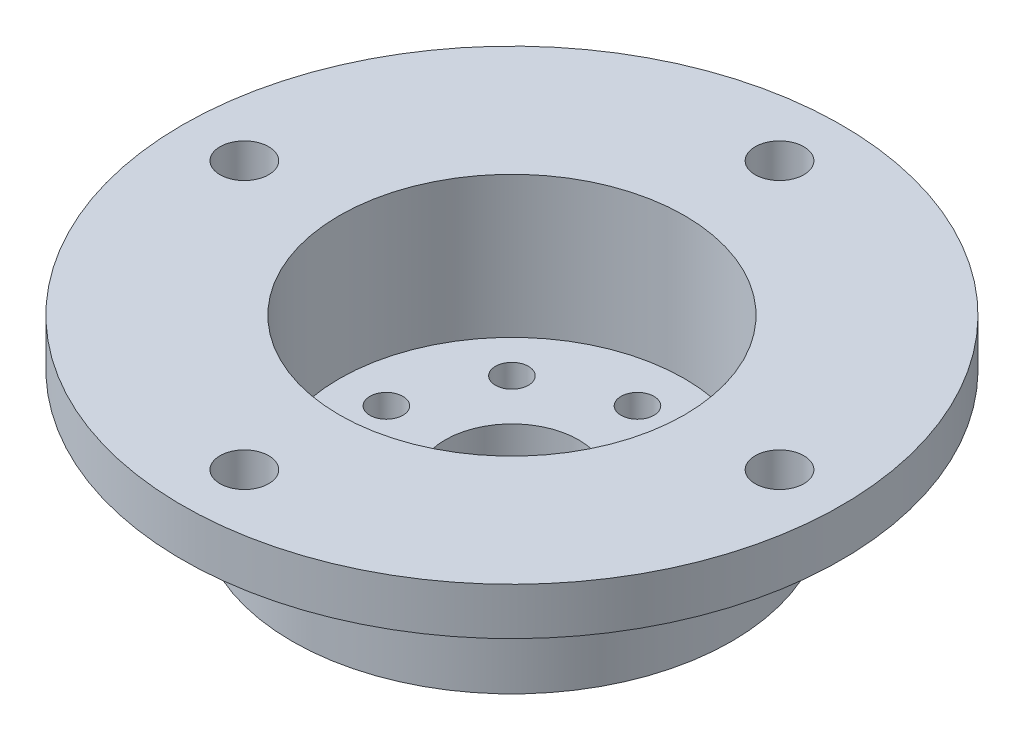
SolidWorks part; units mm, degrees
ref_plane "Plan de face" through (0, 0, 0) normal (0, 0, 1) x (1, 0, 0)
ref_plane "Plan de dessus" through (0, 0, 0) normal (0, 1, 0) x (1, 0, 0)
ref_plane "Plan de droite" through (0, 0, 0) normal (1, 0, 0) x (0, 0, -1)
sketch "Esquisse3" plane through (0, 0, 0) normal (0, 0, 1) x (1, 0, 0)
  line L0 (0, 36.8298) -> (0, -27.7228) construction
  line L1 (-21, 23.3898) -> (-21, 20.3898)
  line L2 (-21, 20.3898) -> (-14, 20.3898)
  line L3 (-14, 20.3898) -> (-14, 12.3898)
  line L4 (-14, 12.3898) -> (-4.25, 12.3898)
  line L5 (-4.25, 12.3898) -> (-4.25, 14.3898)
  line L6 (-4.25, 14.3898) -> (-11, 14.3898)
  line L7 (-11, 14.3898) -> (-11, 23.3898)
  line L8 (-11, 23.3898) -> (-21, 23.3898)
  dimension "D1" = 4.25
  dimension "D2" = 11
  dimension "D3" = 3
  dimension "D4" = 2
  dimension "D5" = 10
  dimension "D6" = 3
  dimension "D7" = 6
revolve "Révolution2" add sketch "Esquisse3" angle 360 about L0
sketch "Esquisse4" plane through (0, 14.3898, 0) normal (0, 1, 0) x (1, 0, 0)
  circle A0 centre (0, 8) radius 1.05
  circle A1 centre (5.6569, 5.6569) radius 1.05
  circle A2 centre (8, 0) radius 1.05
  circle A3 centre (5.6569, -5.6569) radius 1.05
  circle A4 centre (0, -8) radius 1.05
  circle A5 centre (-5.6569, -5.6569) radius 1.05
  circle A6 centre (-8, 0) radius 1.05
  circle A7 centre (-5.6569, 5.6569) radius 1.05
  point P20 (0, 0)
  dimension "D2" = 2.1
  dimension "D1" = 8
  dimension "D3" = 8
extrude "Enlèv. mat.-Extru.1" cut sketch "Esquisse4" against normal through all
sketch "Esquisse5" plane through (0, 20.3898, 0) normal (0, -1, 0) x (1, 0, 0)
  line L0 (0, 0) -> (0, 22.5004) construction
  line L1 (-3.3996, 14) -> (5.6978, 14) construction
  line L2 (-3.3996, 15.5) -> (5.4934, 15.5) construction
  line L3 (-17.05, 0) -> (17.05, 0) construction
  circle A0 centre (0, 17.05) radius 1.55
  circle A1 centre (0, 0) radius 14 construction
  circle A2 centre (0, 0) radius 14 construction
  circle A3 centre (17.05, 0) radius 1.55
  circle A4 centre (0, -17.05) radius 1.55
  circle A5 centre (-17.05, 0) radius 1.55
  point P21 (0, 0)
  dimension "D1" = 3.1
  dimension "D2" = 1.5
  dimension "D3" = 4
extrude "Enlèv. mat.-Extru.2" cut sketch "Esquisse5" against normal through all
